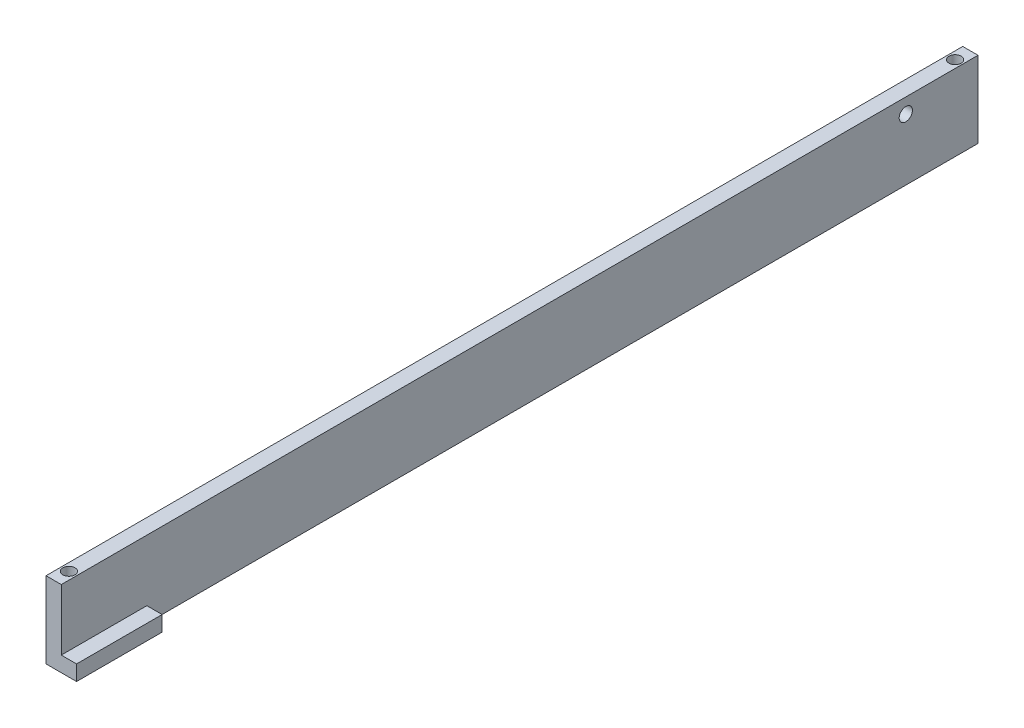
SolidWorks part; units mm, degrees
other "Markup1"
sketch "Sketch6" plane through (0, 0, 0) normal (0.7258, -0.6292, 0.2781) x (-0.261, -0.6259, -0.735)
ref_plane "Front Plane" through (0, 0, 0) normal (0, 0, 1) x (1, 0, 0)
ref_plane "Top Plane" through (0, 0, 0) normal (0, 1, 0) x (1, 0, 0)
ref_plane "Right Plane" through (0, 0, 0) normal (1, 0, 0) x (0, 0, -1)
sketch "Sketch1" plane through (0, 0, 0) normal (0, 0, 1) x (1, 0, 0)
  line L0 (0, 0) -> (-12.7, 0)
  line L1 (-12.7, 0) -> (-12.7, 31.75)
  line L2 (-12.7, 31.75) -> (-6.35, 31.75)
  line L3 (-6.35, 31.75) -> (-6.35, 6.35)
  line L4 (-6.35, 6.35) -> (0, 6.35)
  line L5 (0, 6.35) -> (0, 0)
  dimension "D1" = 6.35
  dimension "D2" = 6.35
  dimension "D3" = 6.35
  dimension "D4" = 25.4
extrude "Boss-Extrude1" add sketch "Sketch1" against normal blind 381
sketch "Sketch2" plane through (-12.7, 0, 0) normal (-1, 0, 0) x (0, 0, 1)
  circle A8 centre (-351, 25.5625) radius 2.75
  circle A9 centre (-351, 25.5625) radius 2.75
  dimension "D7" = 0
extrude "Cut-Extrude1" cut sketch "Sketch2" against normal up to next
sketch "Sketch3" plane through (0, 31.75, 0) normal (0, 1, 0) x (1, 0, 0)
  line L0 (-9.525, 381) -> (-9.525, 0) construction
  line L1 (-6.35, 381) -> (-12.7, 381) construction
  line L2 (-6.35, 0) -> (-12.7, 0) construction
  circle A0 centre (-9.525, 6.35) radius 2.54
  circle A1 centre (-9.525, 374.65) radius 2.54
  dimension "D1" = 5.08
  dimension "D3" = 6.35
  dimension "D2" = 6.35
extrude "Cut-Extrude2" cut sketch "Sketch3" against normal blind 7.62
sketch "Sketch4" plane through (0, 0, 0) normal (0, -1, 0) x (1, 0, 0)
  line L0 (-9.525, 0) -> (-9.525, -381) construction
  line L1 (-12.7, 0) -> (0, 0) construction
  line L2 (-12.7, -381) -> (0, -381) construction
  line L3 (0, -381) -> (0, 0) construction
  circle A0 centre (-9.525, -374.65) radius 2.54
  circle A1 centre (-9.525, -6.35) radius 2.54
  dimension "D2" = 5.08
  dimension "D1" = 9.525
  dimension "D3" = 6.35
  dimension "D4" = 6.35
extrude "Cut-Extrude3" cut sketch "Sketch4" against normal blind 7.62
sketch "Sketch5" plane through (0, 0, -381) normal (0, 0, -1) x (-1, 0, 0)
  line L1 (6.35, 6.35) -> (0, 6.35)
  line L2 (6.35, 6.35) -> (6.35, 0)
  line L3 (6.35, 0) -> (0, 0)
  line L4 (0, 6.35) -> (0, 0)
extrude "Cut-Extrude4" cut sketch "Sketch5" against normal blind 345.44
